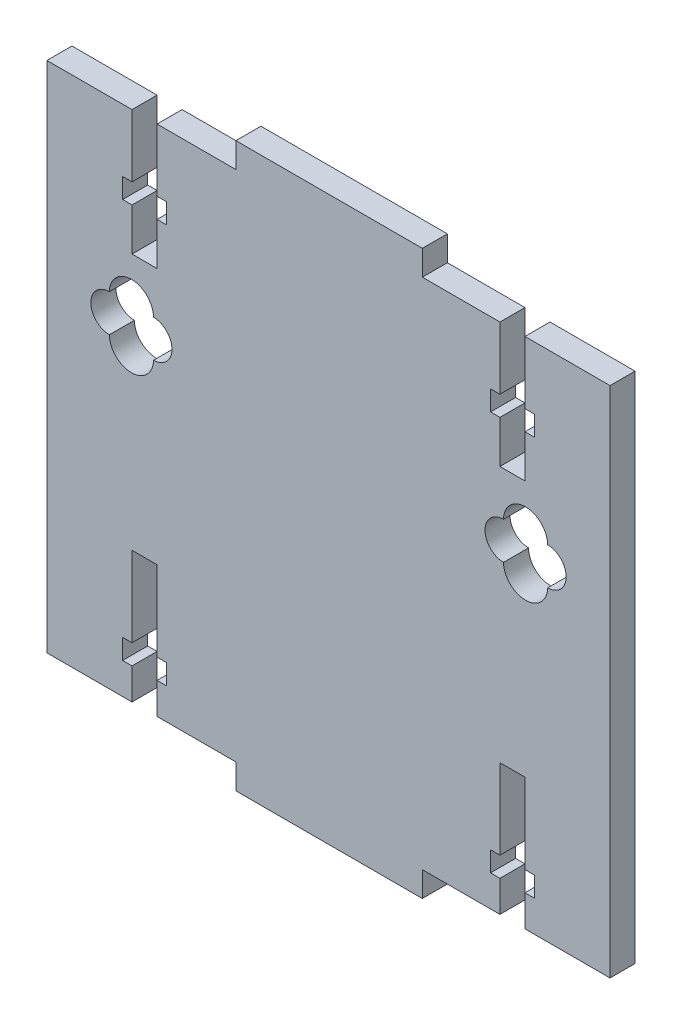
SolidWorks part; units mm, degrees
ref_plane "Front Plane" through (0, 0, 0) normal (0, 0, 1) x (1, 0, 0)
ref_plane "Top Plane" through (0, 0, 0) normal (0, 1, 0) x (1, 0, 0)
ref_plane "Right Plane" through (0, 0, 0) normal (1, 0, 0) x (0, 0, -1)
sketch "Sketch1" plane through (0, 0, 0) normal (0, 0, 1) x (1, 0, 0)
  line L1 (-45, 41) -> (45, 41)
  line L2 (-45, 41) -> (-45, -41)
  line L3 (-45, -41) -> (45, -41)
  line L4 (45, 41) -> (45, -41)
  dimension "D1" = 90
  dimension "D2" = 82
  dimension "D3" = 45
  dimension "D4" = 41
extrude "Boss-Extrude1" add sketch "Sketch1" along normal blind 4
sketch "Sketch4" plane through (0, 0, 4) normal (0, 0, 1) x (1, 0, 0)
  line L0 (45, -41) -> (45, 41) construction
  line L1 (15, 41) -> (-14.8, 41)
  line L2 (15, 41) -> (15, 45)
  line L3 (15, 45) -> (-14.8, 45)
  line L4 (-14.8, 41) -> (-14.8, 45)
  line L5 (45, 41) -> (-45, 41) construction
  dimension "D1" = 30
  dimension "D2" = 4
  dimension "D3" = 29.8
extrude "Boss-Extrude2" add sketch "Sketch4" against normal blind 4
ref_plane "Plane1" through (0, 0, 0) normal (0, -1, 0) x (-1, 0, 0)
mirror "Mirror1" about plane through (0, 0, 0) normal (0, -1, 0) of "Boss-Extrude2"
sketch "Sketch5" plane through (0, 0, 4) normal (0, 0, 1) x (1, 0, 0)
  line L0 (0, 0) -> (0, 51.0938) construction
  line L1 (0, 0) -> (63.9395, 0) construction
  line L2 (27.4, 41) -> (27.4, 31)
  line L3 (-45, -41) -> (-14.8, -41) construction
  line L16 (29.4, 41) -> (29.4, 28.1548) construction
  line L18 (31.4, 27.8) -> (31.4, 21)
  line L22 (32.9, 27.8) -> (31.4, 27.8)
  line L23 (32.9, 31) -> (32.9, 27.8)
  line L24 (31.4, 31) -> (32.9, 31)
  line L25 (31.4, 41) -> (27.4, 41)
  line L28 (31.4, 41) -> (31.4, 31)
  line L29 (29.4, -41) -> (29.4, -26.1548) construction
  line L42 (-29.4, -41) -> (-29.4, -26.1548) construction
  line L55 (31.4, 21) -> (27.4, 21)
  line L56 (27.4, 31) -> (25.9, 31)
  line L57 (25.9, 31) -> (25.9, 27.8)
  line L58 (25.9, 27.8) -> (27.4, 27.8)
  line L59 (27.4, 27.8) -> (27.4, 21)
  line L60 (-29.4, 41) -> (-29.4, 28.1548) construction
  line L61 (-27.4, 27.8) -> (-27.4, 21)
  line L62 (-25.9, 27.8) -> (-27.4, 27.8)
  line L63 (-25.9, 31) -> (-25.9, 27.8)
  line L64 (-27.4, 31) -> (-25.9, 31)
  line L65 (-31.4, 21) -> (-27.4, 21)
  line L66 (-31.4, 41) -> (-31.4, 31)
  line L67 (-31.4, 41) -> (-27.4, 41)
  line L68 (-31.4, 31) -> (-32.9, 31)
  line L69 (-32.9, 31) -> (-32.9, 27.8)
  line L70 (-32.9, 27.8) -> (-31.4, 27.8)
  line L71 (-31.4, 27.8) -> (-31.4, 21)
  line L72 (-27.4, 41) -> (-27.4, 31)
  line L73 (-27.4, -36) -> (-27.4, -41)
  line L74 (31.4, -41) -> (31.4, -36)
  line L75 (-31.4, -32.8) -> (-31.4, -20)
  line L76 (-25.9, -32.8) -> (-27.4, -32.8)
  line L77 (-25.9, -36) -> (-25.9, -32.8)
  line L78 (-27.4, -36) -> (-25.9, -36)
  line L79 (-32.9, -32.8) -> (-31.4, -32.8)
  line L80 (-32.9, -36) -> (-32.9, -32.8)
  line L81 (-31.4, -36) -> (-32.9, -36)
  line L82 (-31.4, -41) -> (-27.4, -41)
  line L83 (-27.4, -20) -> (-27.4, -32.8)
  line L84 (-31.4, -20) -> (-27.4, -20)
  line L85 (-31.4, -41) -> (-31.4, -36)
  line L86 (45, 41) -> (15, 41) construction
  line L87 (31.4, -20) -> (27.4, -20)
  line L88 (27.4, -20) -> (27.4, -32.8)
  line L89 (31.4, -41) -> (27.4, -41)
  line L90 (31.4, -36) -> (32.9, -36)
  line L91 (32.9, -36) -> (32.9, -32.8)
  line L92 (32.9, -32.8) -> (31.4, -32.8)
  line L93 (27.4, -36) -> (25.9, -36)
  line L94 (25.9, -36) -> (25.9, -32.8)
  line L95 (25.9, -32.8) -> (27.4, -32.8)
  line L96 (31.4, -32.8) -> (31.4, -20)
  line L97 (27.4, -36) -> (27.4, -41)
  point P8 (29.4, 21)
  point P63 (-29.4, 21)
  dimension "D1" = 3.2
  dimension "D2" = 2
  dimension "D4" = 1.5
  dimension "D5" = 12.8
  dimension "D6" = 3.2
  dimension "D7" = 5
  dimension "D8" = 27.4
  dimension "D9" = 20
  dimension "D10" = 10
  dimension "D11" = 2
  dimension "D12" = 4
  dimension "D13" = 1.5
  dimension "D14" = 1.5
  dimension "D15" = 27.4
extrude "Cut-Extrude1" cut sketch "Sketch5" against normal blind 10
sketch "Sketch6" plane through (0, 0, 4) normal (0, 0, 1) x (1, 0, 0)
  line L0 (-35, 11) -> (-28, 11) construction
  line L3 (-31.5, 13.933) -> (-31.5, 8.067) construction
  line L6 (0, 0) -> (0, 16.3078) construction
  line L9 (31.5, 13.933) -> (31.5, 8.067) construction
  line L16 (35, 11) -> (28, 11) construction
  arc A4 (27.9698, 8.0159) -> (27.9698, 13.9841) centre (28, 11) cw
  arc A5 (-27.9698, 13.9841) -> (-35.0302, 13.9841) centre (-31.5, 13.933) ccw
  arc A6 (35.0302, 13.9841) -> (35.0302, 8.0159) centre (35, 11) cw
  arc A7 (-35.0302, 8.0159) -> (-27.9698, 8.0159) centre (-31.5, 8.067) ccw
  arc A8 (35.0302, 8.0159) -> (27.9698, 8.0159) centre (31.5, 8.067) cw
  arc A9 (27.9698, 13.9841) -> (35.0302, 13.9841) centre (31.5, 13.933) cw
  arc A16 (-35.0302, 13.9841) -> (-35.0302, 8.0159) centre (-35, 11) ccw
  arc A17 (-27.9698, 8.0159) -> (-27.9698, 13.9841) centre (-28, 11) ccw
  point P17 (31.5, 11)
  point P24 (-31.5, 11)
  point P29 (-31.5, 11)
extrude "Cut-Extrude2" cut sketch "Sketch6" against normal blind 10
